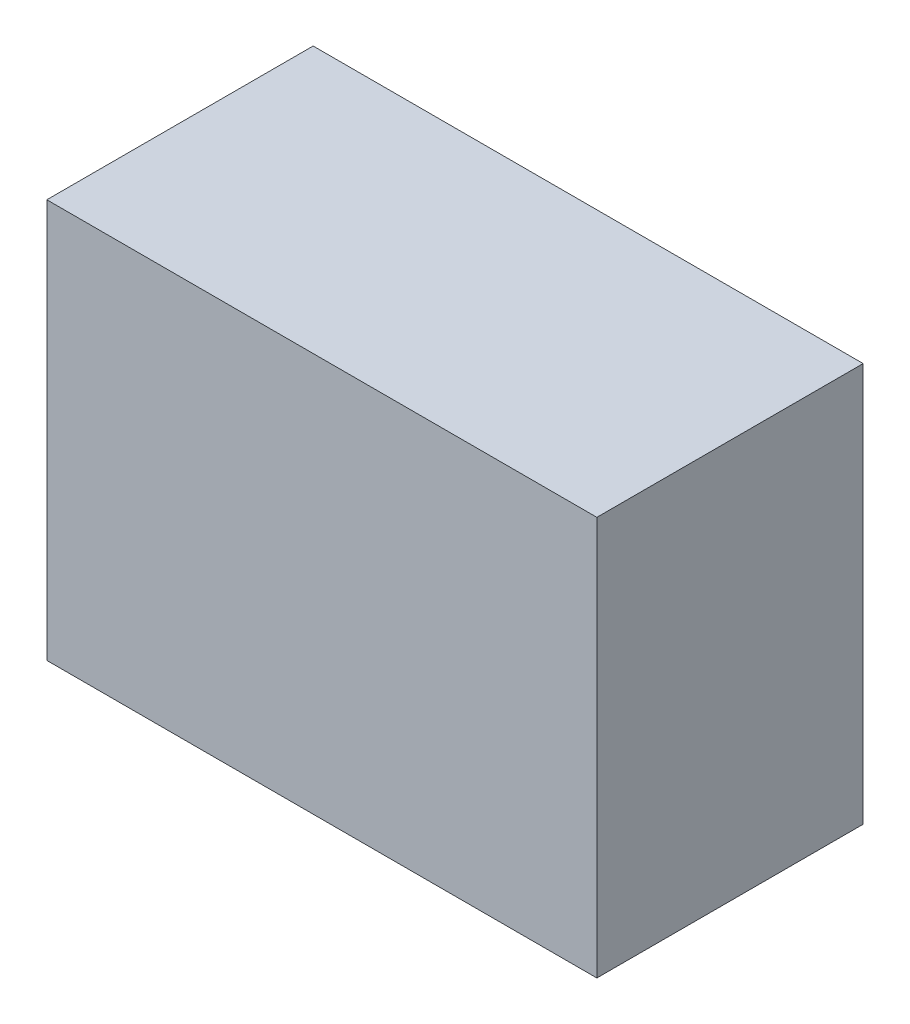
SolidWorks part; units mm, degrees
material "Cast Alloy Steel"
ref_plane "Front Plane" through (0, 0, 0) normal (0, 0, 1) x (1, 0, 0)
ref_plane "Top Plane" through (0, 0, 0) normal (0, 1, 0) x (1, 0, 0)
ref_plane "Right Plane" through (0, 0, 0) normal (1, 0, 0) x (0, 0, -1)
sketch "Sketch1" plane through (0, 0, 0) normal (0, 0, 1) x (1, 0, 0)
  line L1 (-81.8362, -59.3601) -> (81.8362, -59.3601)
  line L2 (-81.8362, -59.3601) -> (-81.8362, 59.3601)
  line L3 (-81.8362, 59.3601) -> (81.8362, 59.3601)
  line L4 (81.8362, -59.3601) -> (81.8362, 59.3601)
  line L5 (-81.8362, -59.3601) -> (81.8362, 59.3601) construction
  line L6 (-81.8362, 59.3601) -> (81.8362, -59.3601) construction
  point P0 (0, 0)
extrude "Boss-Extrude1" add sketch "Sketch1" along normal blind 79.248
